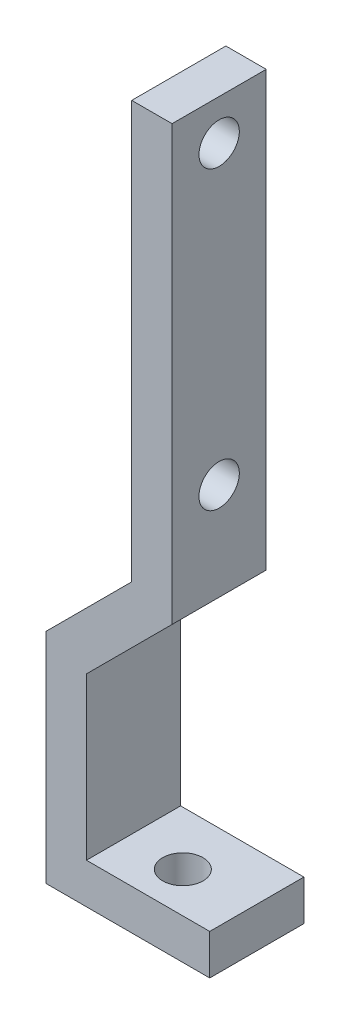
SolidWorks part; units mm, degrees
ref_plane "前视基准面" through (0, 0, 0) normal (0, 0, 1) x (1, 0, 0)
ref_plane "上视基准面" through (0, 0, 0) normal (0, 1, 0) x (1, 0, 0)
ref_plane "右视基准面" through (0, 0, 0) normal (1, 0, 0) x (0, 0, -1)
sketch "草图1" plane through (0, 0, 0) normal (0, 0, 1) x (1, 0, 0)
  line L0 (-3.6411, 21.9867) -> (-3.6411, -9.0133)
  line L1 (-3.6411, -9.0133) -> (-10.005, -15.3772)
  line L2 (-10.005, -15.3772) -> (-10.005, -31.6199)
  line L3 (-10.005, -31.6199) -> (2.1589, -31.6199)
  line L4 (2.1589, -31.6199) -> (2.1589, -28.6199)
  line L5 (2.1589, -28.6199) -> (-7.005, -28.6199)
  line L6 (-7.005, -28.6199) -> (-7.005, -16.6199)
  line L7 (-7.005, -16.6199) -> (-0.6411, -10.2559)
  line L8 (-0.6411, -10.2559) -> (-0.6411, 21.9867)
  line L9 (-0.6411, 21.9867) -> (-3.6411, 21.9867)
  line L10 (-2.8411, -28.6199) -> (-2.8411, -31.6199)
  line L11 (-4.3411, -28.6199) -> (-4.3411, -31.6199)
  line L12 (-1.3411, -28.6199) -> (-1.3411, -31.6199)
  dimension "D1" = 3
  dimension "D2" = 3
  dimension "D3" = 3
  dimension "D4" = 3
  dimension "D5" = 31
  dimension "D6" = 12
  dimension "D7" = 9
  dimension "D8" = 1.5
  dimension "D9" = 1.5
  dimension "D10" = 0.8
  dimension "D11" = 5
extrude "凸台-拉伸1" add sketch "草图1" along normal blind 7 contours L11 L5 L6 L7 L8 L9 L0 L1 L2 L3 | L12 L5 L10 L3 | L5 L11 L3 L10 | L5 L12 L3 L4
sketch "草图2" plane through (-3.6411, 0, 0) normal (-1, 0, 0) x (0, 0, 1)
  line L0 (7, 21.9867) -> (0, 21.9867) construction
  line L1 (0, 21.9867) -> (0, -9.0133) construction
  circle A0 centre (3.5, 18.9867) radius 1.5
  circle A1 centre (3.5, -3.0133) radius 1.5
  dimension "D2" = 3
  dimension "D3" = 3
  dimension "D1" = 3
  dimension "D4" = 22
  dimension "D5" = 3.5
  dimension "D6" = 3.5
extrude "切除-拉伸2" cut sketch "草图2" against normal blind 7
sketch "草图4" plane through (0, -28.6199, 0) normal (0, 1, 0) x (1, 0, 0)
  line L0 (2.1589, 0) -> (-7.005, 0) construction
  line L1 (2.1589, -7) -> (2.1589, 0) construction
  circle A0 centre (-2.8411, -4) radius 1.5
  dimension "D2" = 3
  dimension "D1" = 4
  dimension "D3" = 5
extrude "切除-拉伸3" cut sketch "草图4" against normal blind 7
